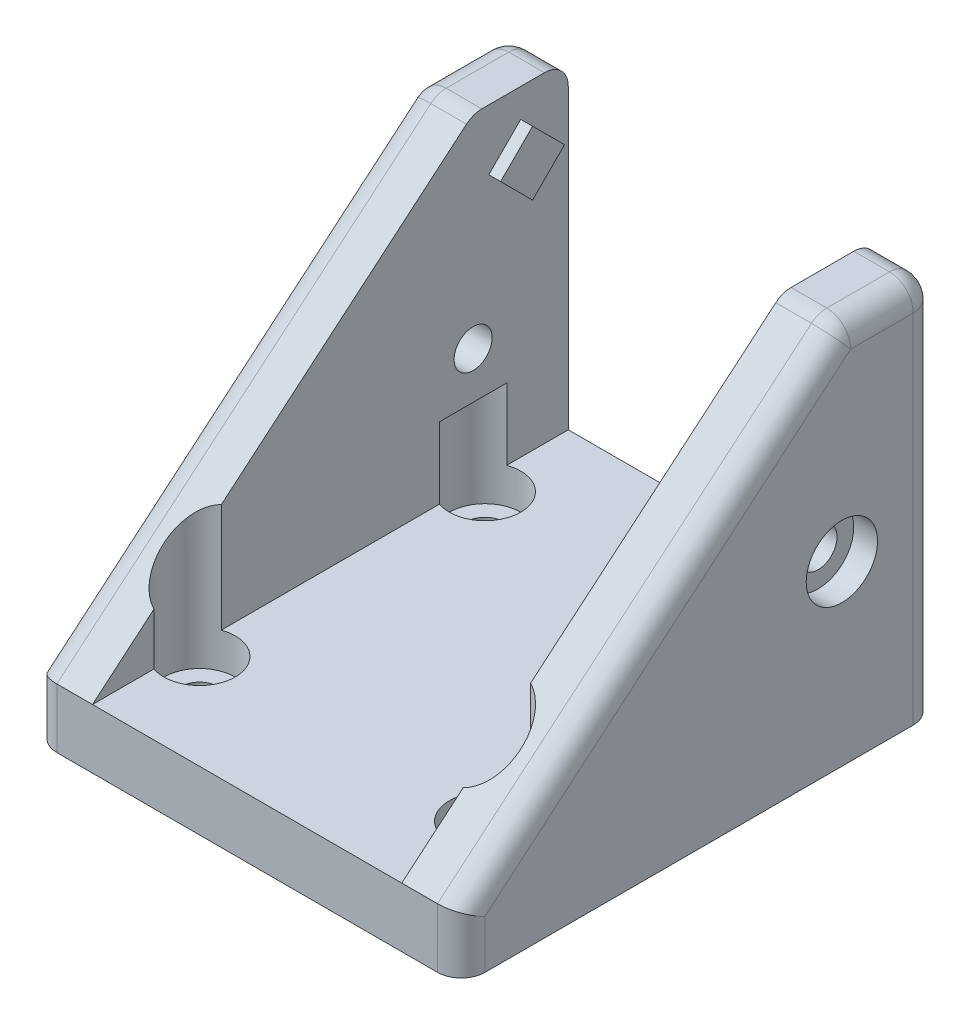
SolidWorks part; units mm, degrees
ref_plane "前视基准面" through (0, 0, 0) normal (0, 0, 1) x (1, 0, 0)
ref_plane "上视基准面" through (0, 0, 0) normal (0, 1, 0) x (1, 0, 0)
ref_plane "右视基准面" through (0, 0, 0) normal (1, 0, 0) x (0, 0, -1)
sketch "Sketch1" plane through (0, 0, 0) normal (0, 1, 0) x (1, 0, 0)
  line L1 (-18, -20) -> (18, -20)
  line L2 (-18, -20) -> (-18, 20)
  line L3 (-18, 20) -> (18, 20)
  line L4 (18, -20) -> (18, 20)
  line L5 (-18, -20) -> (18, 20) construction
  line L6 (-18, 20) -> (18, -20) construction
  point P0 (0, 0)
  dimension "D1" = 36
  dimension "D2" = 40
extrude "Extrude1" add sketch "Sketch1" along normal blind 5
sketch "Sketch2" plane through (-18, 0, 0) normal (-1, 0, 0) x (0, 0, 1)
  line L0 (-20, 0) -> (-20, 32)
  line L1 (-20, 32) -> (-12, 32)
  line L2 (-12, 32) -> (20, 5)
  line L3 (20, 5) -> (20, 0)
  line L4 (20, 0) -> (-20, 0)
  dimension "D1" = 32
  dimension "D2" = 8
extrude "Extrude2" add sketch "Sketch2" against normal blind 5
sketch "Sketch3" plane through (18, 0, 0) normal (1, 0, 0) x (0, 0, -1)
  line L0 (20, 0) -> (20, 32)
  line L1 (20, 32) -> (12, 32)
  line L2 (12, 32) -> (-20, 5)
  line L3 (-20, 5) -> (-20, 0)
  line L4 (-20, 0) -> (20, 0)
extrude "Extrude3" add sketch "Sketch3" against normal blind 5
sketch "Sketch4" plane through (0, 5, 0) normal (0, 1, 0) x (1, 0, 0)
  line L0 (-23.8853, 0) -> (24.0338, 0) construction
  line L1 (0, 22.3103) -> (0, -24.2227) construction
  line L2 (13, 20) -> (-13, 20) construction
  circle A0 centre (-12, 12) radius 3
  circle A1 centre (-12, -12) radius 3
  circle A2 centre (12, 12) radius 3
  circle A3 centre (12, -12) radius 3
  dimension "D3" = 6
  dimension "D1" = 24
  dimension "D2" = 24
  dimension "D4" = 8
  dimension "D5" = 24
extrude "Extrude4" cut sketch "Sketch4" against normal blind 3
sketch "Sketch5" plane through (0, 2, 0) normal (0, 1, 0) x (1, 0, 0)
  circle A0 centre (-12, 12) radius 1.6
  circle A1 centre (-12, -12) radius 1.6
  circle A2 centre (12, -12) radius 1.6
  circle A3 centre (12, 12) radius 1.6
  dimension "D1" = 3.2
extrude "Extrude5" cut sketch "Sketch5" against normal blind 3
sketch "Sketch6" plane through (0, 5, 0) normal (0, 1, 0) x (1, 0, 0)
  circle A0 centre (-12, 12) radius 3
  circle A1 centre (12, 12) radius 3
extrude "Extrude6" cut sketch "Sketch6" along normal blind 6
fillet "Fillet1" radius 2 4 edges at (-15.5, 32, -12) (15.5, 32, -12) (-15.5, 32, -20) (15.5, 32, -20)
sketch "Sketch7" plane through (-13, 0, 0) normal (1, 0, 0) x (0, 0, -1)
  line L0 (16, 32.915) -> (16, -0.9786) construction
  line L1 (16, 29.6005) -> (13.313, 26.9134)
  line L2 (13.313, 26.9134) -> (16, 24.2264)
  line L3 (16, 24.2264) -> (18.687, 26.9134)
  line L4 (18.687, 26.9134) -> (16, 29.6005)
  line L5 (4.7101, 26.9134) -> (20.8907, 26.9134) construction
  line L6 (20, 30) -> (20, 0) construction
  circle A0 centre (16, 26.9134) radius 1.9 construction
  dimension "D1" = 3.8
  dimension "D2" = 4
extrude "Extrude7" add sketch "Sketch7" along normal blind 1
sketch "Sketch9" plane through (-13, 0, 0) normal (1, 0, 0) x (0, 0, -1)
  line L0 (13.313, 26.9134) -> (18.687, 26.9134) construction
  line L1 (16, 29.6005) -> (16, 24.2264) construction
  circle A0 centre (12, 14.9134) radius 1.6
  point P10 (16, 26.9134)
  dimension "D1" = 3.2
  dimension "D2" = 12
  dimension "D3" = 4
extrude "Extrude8" cut sketch "Sketch9" against normal through all
sketch "Sketch10" plane through (-18, 0, 0) normal (-1, 0, 0) x (0, 0, 1)
  circle A0 centre (-12, 14.9134) radius 3
  dimension "D1" = 6
extrude "Extrude9" cut sketch "Sketch10" against normal blind 2
mirror "Mirror2" about plane through (0, 0, 0) normal (1, 0, 0) of "Extrude9", "Extrude8", "Extrude7"
sketch "Sketch11" plane through (0, 5, 0) normal (0, 1, 0) x (1, 0, 0)
  circle A0 centre (-12, -12) radius 3
  circle A1 centre (12, -12) radius 3
extrude "Extrude10" cut sketch "Sketch11" along normal through all
fillet "Fillet2" radius 2 12 edges at (18, 18.2643, 4.2794) (18, 31.8785, -12.0444) (18, 32, -15.3655) (18, 31.4142, -19.4142) (-18, 18.2643, 4.2794) (-18, 31.8785, -12.0444) (-18, 32, -15.3655) (-18, 31.4142, -19.4142) (18, 15, -20) (-18, 15, -20) (18, 2.5, 20) (-18, 2.5, 20)
